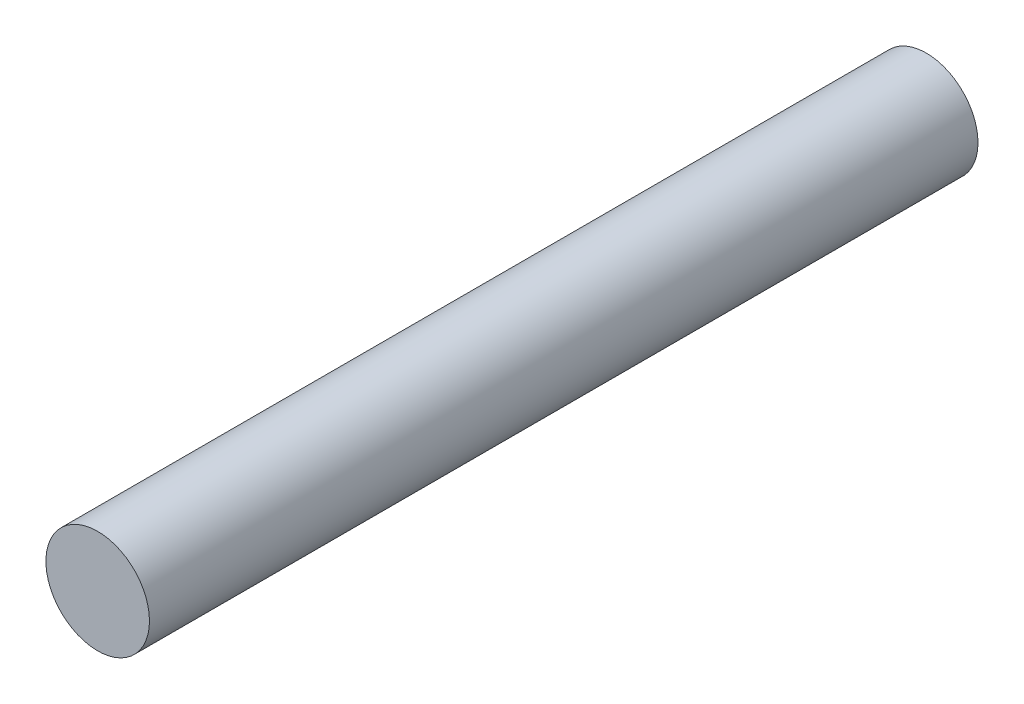
SolidWorks part; units mm, degrees
ref_plane "Plano frontal" through (0, 0, 0) normal (0, 0, 1) x (1, 0, 0)
ref_plane "Plano superior" through (0, 0, 0) normal (0, 1, 0) x (1, 0, 0)
ref_plane "Plano direito" through (0, 0, 0) normal (1, 0, 0) x (0, 0, -1)
sketch "Esboço1" plane through (0, 0, 0) normal (0, 0, 1) x (1, 0, 0)
  circle A0 centre (0, 0) radius 2.5
extrude "Ressalto-extrusão1" add sketch "Esboço1" along normal blind 40
